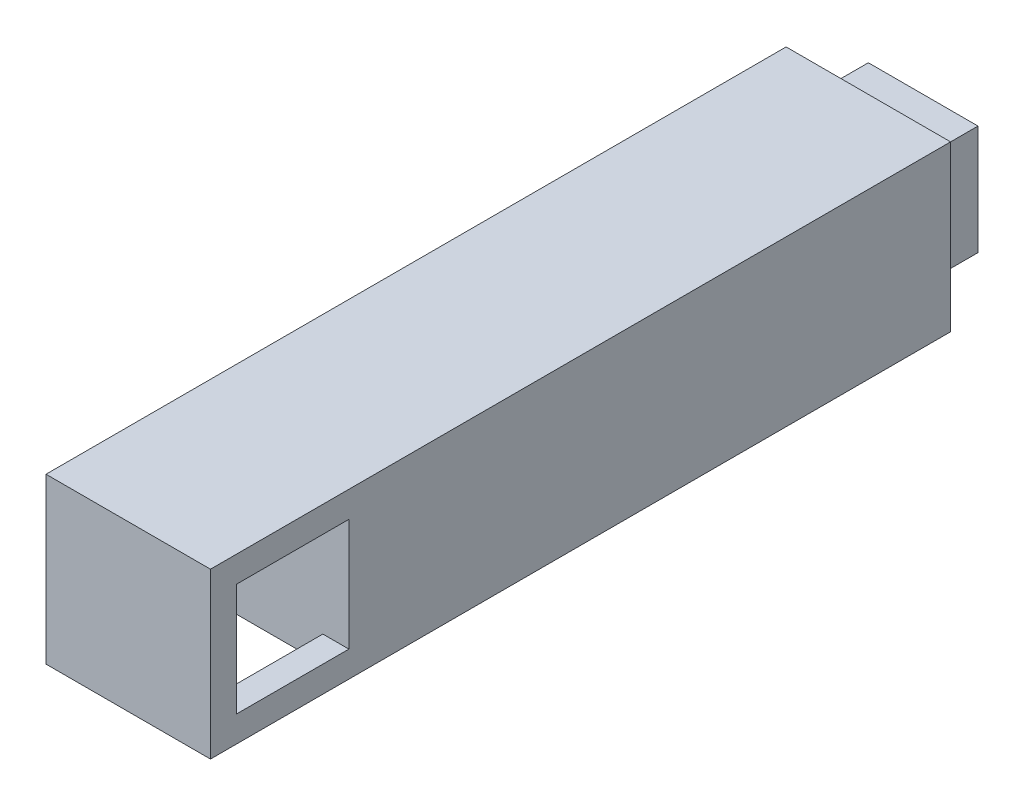
SolidWorks part; units mm, degrees
ref_plane "Front Plane" through (0, 0, 0) normal (0, 0, 1) x (1, 0, 0)
ref_plane "Top Plane" through (0, 0, 0) normal (0, 1, 0) x (1, 0, 0)
ref_plane "Right Plane" through (0, 0, 0) normal (1, 0, 0) x (0, 0, -1)
sketch "Sketch1" plane through (0, 0, 0) normal (0, 0, 1) x (1, 0, 0)
  line L1 (-15, -15) -> (15, -15)
  line L2 (-15, -15) -> (-15, 15)
  line L3 (-15, 15) -> (15, 15)
  line L4 (15, -15) -> (15, 15)
extrude "Boss-Extrude1" add sketch "Sketch1" along normal blind 135
sketch "Sketch2" plane through (0, 0, 0) normal (0, 0, 1) x (1, 0, 0)
  line L1 (-10, -10) -> (10, -10)
  line L2 (-10, -10) -> (-10, 10)
  line L3 (-10, 10) -> (10, 10)
  line L4 (10, -10) -> (10, 10)
extrude "Boss-Extrude2" add sketch "Sketch2" against normal blind 10
sketch "Sketch3" plane through (15, 0, 0) normal (1, 0, 0) x (0, 0, -1)
  line L0 (-130.25, -10.25) -> (-109.75, -10.25)
  line L1 (-109.75, -10.25) -> (-109.75, 10.25)
  line L2 (-109.75, 10.25) -> (-130.25, 10.25)
  line L3 (-130.25, 10.25) -> (-130.25, -10.25)
extrude "Cut-Extrude1" cut sketch "Sketch3" against normal blind 15
sketch "Sketch4" plane through (0, -15, 0) normal (0, -1, 0) x (1, 0, 0)
  line L0 (-10.25, 109.75) -> (10.25, 109.75)
  line L1 (10.25, 109.75) -> (10.25, 130.25)
  line L2 (10.25, 130.25) -> (-10.25, 130.25)
  line L3 (-10.25, 130.25) -> (-10.25, 109.75)
extrude "Cut-Extrude3" cut sketch "Sketch4" against normal blind 15
